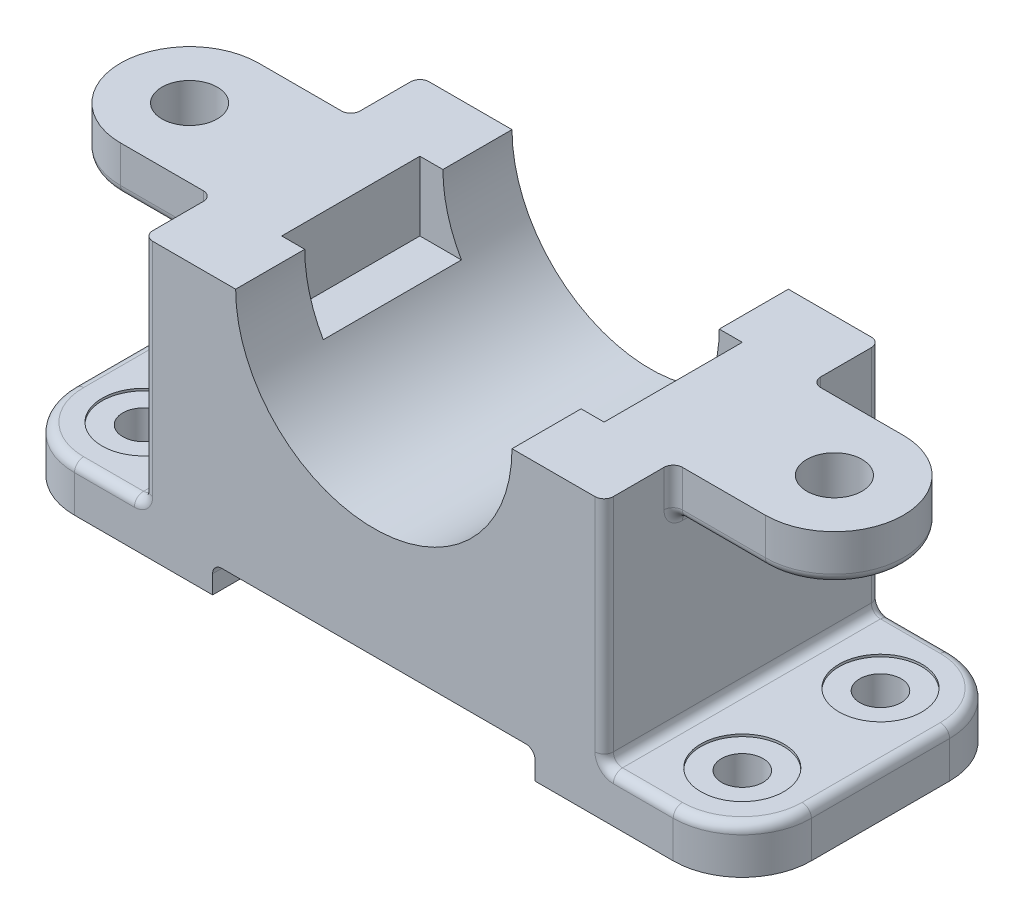
SolidWorks part; units mm, degrees
ref_plane "前视基准面" through (0, 0, 0) normal (0, 0, 1) x (1, 0, 0)
ref_plane "上视基准面" through (0, 0, 0) normal (0, 1, 0) x (1, 0, 0)
ref_plane "右视基准面" through (0, 0, 0) normal (1, 0, 0) x (0, 0, -1)
ref_plane "基准面4" through (0, 54, 0) normal (0, 1, 0) x (1, 0, 0)
sketch "草图1" plane through (0, 54, 0) normal (0, 1, 0) x (1, 0, 0)
  line L0 (80, 30) -> (-80, 30)
  line L1 (-80, 30) -> (-80, -30)
  line L2 (-80, -30) -> (80, -30)
  line L3 (80, -30) -> (80, 30)
extrude "凸台-拉伸1" add sketch "草图1" against normal blind 60
sketch "草图2" plane through (0, 0, -30) normal (0, 0, -1) x (-1, 0, 0)
  line L0 (-50, 4) -> (-50, 54)
  line L1 (-50, 54) -> (-80, 54)
  line L2 (-80, 54) -> (-80, 4)
  line L3 (-80, 4) -> (-50, 4)
extrude "切除-拉伸1" cut sketch "草图2" against normal through all
sketch "草图3" plane through (0, 0, -30) normal (0, 0, -1) x (-1, 0, 0)
  line L0 (50, 54) -> (50, 4)
  line L1 (50, 4) -> (80, 4)
  line L2 (80, 4) -> (80, 54)
  line L3 (80, 54) -> (50, 54)
extrude "切除-拉伸2" cut sketch "草图3" against normal through all
sketch "草图4" plane through (0, 0, -30) normal (0, 0, -1) x (-1, 0, 0)
  line L0 (35, -6) -> (35, 0)
  line L1 (35, 0) -> (-35, 0)
  line L2 (-35, 0) -> (-35, -6)
  line L3 (-35, -6) -> (35, -6)
extrude "切除-拉伸3" cut sketch "草图4" against normal through all
sketch "草图5" plane through (0, 54, 0) normal (0, 1, 0) x (1, 0, 0)
  line L0 (-50, -15) -> (-50, 15)
  line L1 (-50, 15) -> (-70, 15)
  line L2 (-70, -15) -> (-50, -15)
  arc A0 (-70, 15) -> (-70, -15) centre (-70, 0) ccw
extrude "凸台-拉伸2" add sketch "草图5" against normal blind 10
sketch "草图6" plane through (0, 54, 0) normal (0, 1, 0) x (1, 0, 0)
  line L0 (50, 15) -> (50, -15)
  line L1 (50, -15) -> (70, -15)
  line L2 (70, 15) -> (50, 15)
  arc A0 (70, -15) -> (70, 15) centre (70, 0) ccw
extrude "凸台-拉伸3" add sketch "草图6" against normal blind 10
sketch "草图7" plane through (0, 54, 0) normal (0, 1, 0) x (-1, 0, 0)
  line L0 (35, 15) -> (-35, 15)
  line L1 (-35, 15) -> (-35, -15)
  line L2 (-35, -15) -> (35, -15)
  line L3 (35, -15) -> (35, 15)
extrude "切除-拉伸4" cut sketch "草图7" against normal blind 15
hole_wizard "M52 间隙孔1" positions "草图9" profile "草图8" hole size "M52" standard "ANSI Metric"
sketch "草图9" plane through (0, 0, -30) normal (0, 0, -1) x (-1, 0, 0)
  point P0 (0, 54)
sketch "草图8" plane through (0, 54, -30) normal (1, 0, 0) x (0, 1, 0)
  line L0 (0, 0) -> (0, 60)
  line L1 (0, 60) -> (30, 60)
  line L2 (30, 60) -> (30, 0)
  line L5 (30, 0) -> (0, 0)
  line L11 (0, -6.35) -> (0, 107.95) construction
  dimension "通孔孔直径" = 60
  dimension "通孔孔深度" = 60
hole_wizard "Ø12.0 (12) 直径孔1" positions "草图11" profile "草图10" hole size "Ø12.0" standard "ANSI Metric"
sketch "草图11" plane through (0, 44, 0) normal (0, -1, 0) x (-1, 0, 0)
  point P0 (-70, 0)
sketch "草图10" plane through (70, 44, 0) normal (1, 0, 0) x (0, 0, -1)
  line L0 (0, 0) -> (0, 10)
  line L1 (0, 10) -> (6, 10)
  line L2 (6, 10) -> (6, 0)
  line L5 (6, 0) -> (0, 0)
  line L11 (0, -6.35) -> (0, 107.95) construction
  dimension "通孔孔直径" = 12
  dimension "通孔孔深度" = 10
hole_wizard "Ø12.0 (12) 直径孔2" positions "草图13" profile "草图12" hole size "Ø12.0" standard "ANSI Metric"
sketch "草图13" plane through (0, 54, 0) normal (0, 1, 0) x (1, 0, 0)
  point P0 (-70, 0)
sketch "草图12" plane through (-70, 54, 0) normal (1, 0, 0) x (0, 0, 1)
  line L0 (0, 0) -> (0, 10)
  line L1 (0, 10) -> (6, 10)
  line L2 (6, 10) -> (6, 0)
  line L5 (6, 0) -> (0, 0)
  line L11 (0, -6.35) -> (0, 107.95) construction
  dimension "通孔孔直径" = 12
  dimension "通孔孔深度" = 10
hole_wizard "M8 六角头螺栓的柱形沉头孔1" positions "草图15" profile "草图14" counterbore size "M8" standard "ANSI Metric"
sketch "草图15" plane through (0, 4, 0) normal (0, 1, 0) x (1, 0, 0)
  point P0 (-65, -15)
  point P1 (-65, 15)
  point P2 (65, 15)
  point P3 (65, -15)
sketch "草图14" plane through (-65, 4, 15) normal (1, 0, 0) x (0, 0, 1)
  line L0 (0, 0) -> (0, 10)
  line L1 (0, 10) -> (4.5, 10)
  line L3 (4.5, 10) -> (4.5, 0.5)
  line L4 (4.5, 0.5) -> (9, 0.5)
  line L5 (9, 0.5) -> (9, 0)
  line L7 (9, 0) -> (0, 0)
  line L11 (0, -6.35) -> (0, 107.95) construction
  dimension "通孔孔直径" = 9
  dimension "通孔孔深度" = 10
  dimension "柱形沉头孔直径" = 18
  dimension "柱形沉头孔深度" = 0.5
fillet "圆角1" radius 15 4 edges at (80, -1, -30) (80, -1, 30) (-80, -1, -30) (-80, -1, 30)
fillet "圆角2" radius 2 30 edges at (-50, 49, 15) (-50, 44, 0) (-50, 49, -15) (-50, 29, 30) (-50, 4, 0) (-57.5, 4, 30) (-75.6066, 4, 25.6066) (-50, 29, -30) (-80, 4, 0) (-75.6066, 4, -25.6066) (-57.5, 4, -30) (50, 49, 15) (50, 44, 0) (50, 49, -15) (50, 29, 30) (57.5, 4, 30) (75.6066, 4, 25.6066) (80, 4, 0) (75.6066, 4, -25.6066) (57.5, 4, -30) (50, 29, -30) (60, 44, 15) (60, 44, -15) (85, 44, 0) (-35, 0, 0) (-60, 44, -15) (-60, 44, 15) (-85, 44, 0) (35, 0, 0) (50, 4, 0)
